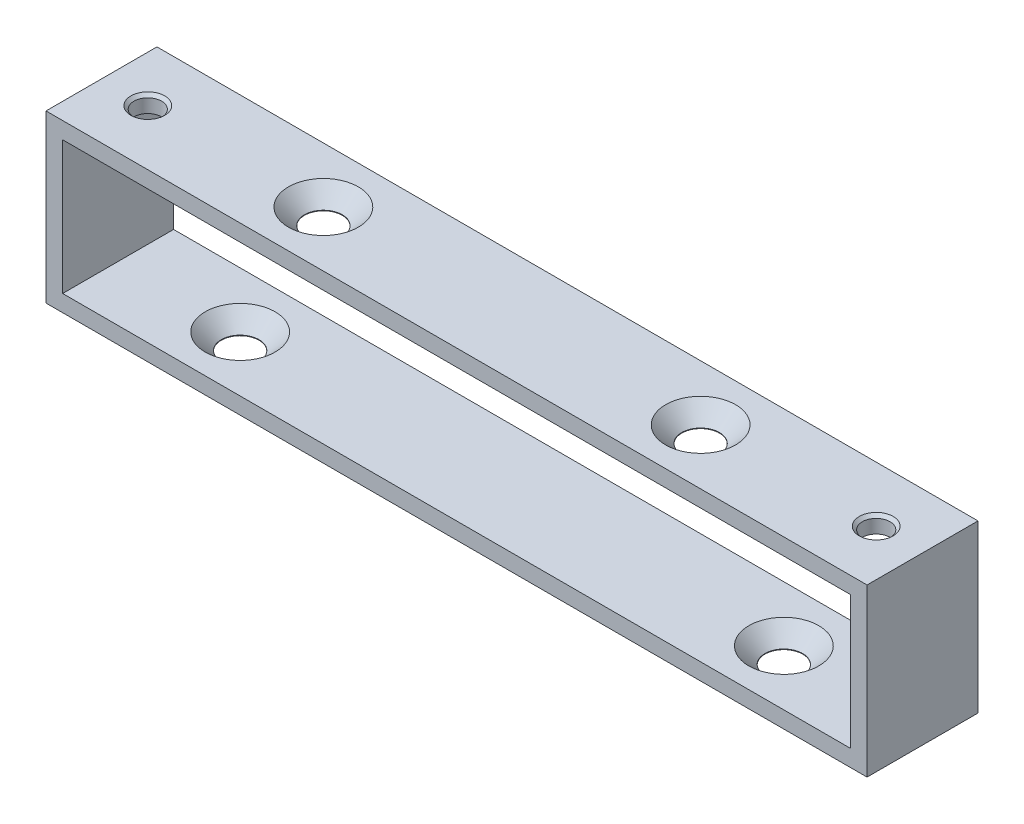
SolidWorks part; units mm, degrees
ref_plane "Ebene vorne" through (0, 0, 0) normal (0, 0, 1) x (1, 0, 0)
ref_plane "Ebene oben" through (0, 0, 0) normal (0, 1, 0) x (1, 0, 0)
ref_plane "Ebene rechts" through (0, 0, 0) normal (1, 0, 0) x (0, 0, -1)
sketch "Skizze1" plane through (0, 0, 0) normal (0, 0, 1) x (1, 0, 0)
  line L1 (-16.6079, 3.6552) -> (57.3921, 3.6552)
  line L2 (-16.6079, 3.6552) -> (-16.6079, -11.3448)
  line L3 (-16.6079, -11.3448) -> (57.3921, -11.3448)
  line L4 (57.3921, 3.6552) -> (57.3921, -11.3448)
  dimension "D1" = 15
  dimension "D2" = 74
extrude "Aufsatz-Linear austragen1" add sketch "Skizze1" along normal blind 10
sketch "Skizze2" plane through (0, 0, 10) normal (0, 0, 1) x (1, 0, 0)
  line L0 (-16.6079, 3.6552) -> (-16.6079, -11.3448) construction
  line L1 (-15.1079, 2.1552) -> (55.8921, 2.1552)
  line L2 (-15.1079, 2.1552) -> (-15.1079, -9.8448)
  line L3 (-15.1079, -9.8448) -> (55.8921, -9.8448)
  line L4 (55.8921, 2.1552) -> (55.8921, -9.8448)
  line L5 (57.3921, 3.6552) -> (-16.6079, 3.6552) construction
  dimension "D1" = 71
  dimension "D2" = 12
  dimension "D3" = 1.5
  dimension "D4" = 1.5
extrude "Schnitt-Linear austragen1" cut sketch "Skizze2" against normal up to next
sketch "Skizze3" plane through (0, 3.6552, 0) normal (0, 1, 0) x (1, 0, 0)
  line L0 (57.3921, -10) -> (-16.6079, -10) construction
  line L1 (57.3921, -10) -> (57.3921, 0) construction
  line L2 (-16.6079, -10) -> (-16.6079, 0) construction
  point P0 (-12.4329, -5)
  point P1 (53.2171, -5)
  dimension "D1" = 5
  dimension "D2" = 65.65
  dimension "D3" = 4.175
  dimension "D4" = 4.175
  dimension "D5" = 5
sketch "Skizze6" plane through (0, -9.8448, 0) normal (0, 1, 0) x (1, 0, 0)
  line L0 (-15.1079, -10) -> (55.8921, -10) construction
  line L1 (-16.6079, -10) -> (-16.6079, 0) construction
  line L2 (57.3921, -10) -> (57.3921, 0) construction
  line L4 (-16.6079, -10) -> (57.3921, -10) construction
  point P0 (-12.4329, -3.63)
  point P1 (53.2171, -3.63)
  dimension "D1" = 6.37
  dimension "D2" = 6.37
  dimension "D3" = 65.65
  dimension "D4" = 4.175
  dimension "D5" = 4.175
sketch "Skizze9" plane through (0, 3.6552, 0) normal (0, 1, 0) x (1, 0, 0)
  line L0 (57.3921, -10) -> (-16.6079, -10) construction
  line L1 (-16.6079, -10) -> (-16.6079, 0) construction
  line L2 (57.3921, -10) -> (57.3921, 0) construction
  point P0 (3.3921, -5)
  point P1 (37.3921, -5)
  dimension "D1" = 5
  dimension "D2" = 5
  dimension "D3" = 20
  dimension "D4" = 20
hole_wizard "Formsenkung für M3 Linsensenkschraube mit Schlitz2" positions "3D-Skizze3" profile "Skizze10" countersink size "M3" standard "ISO" end condition up to next
sketch3d "3D-Skizze3"
  point P0 (3.3921, 3.6552, 5)
  point P3 (37.3921, 3.6552, 5)
sketch "Skizze10" plane through (3.3921, 3.6552, 5) normal (1, 0, 0) x (0, 0, 1)
  line L0 (0, 0) -> (0, 1.5)
  line L1 (0, 1.5) -> (1.7, 1.5)
  line L2 (1.7, 1.5) -> (1.7, 1.45)
  line L3 (1.7, 1.45) -> (3.15, 0)
  line L5 (3.15, 0) -> (0, 0)
  line L6 (-1.7, 1.45) -> (-3.15, 0) construction
  line L11 (0, -6.35) -> (0, 107.95) construction
  dimension "Bohrerdurchmesser" = 3.4
  dimension "Bohrungstiefe" = 1.5
  dimension "Senkdurchmesser (Oben)" = 6.3
  dimension "Senkwinkel (Oben)" = 90
hole_wizard "M3 Gewindebohrung1" positions "3D-Skizze5" profile "Skizze12" tap size "M3" standard "ISO" end condition up to next
sketch3d "3D-Skizze5"
  point P0 (53.2171, 3.6552, 5)
  point P3 (-12.4329, 3.6552, 5)
sketch "Skizze12" plane through (53.2171, 3.6552, 5) normal (1, 0, 0) x (0, 0, 1)
  line L0 (0, 0) -> (0, 1.5)
  line L1 (0, 1.5) -> (1.25, 1.5)
  line L2 (1.25, 1.5) -> (1.25, 0.275)
  line L3 (1.25, 0.275) -> (1.525, 0)
  line L5 (1.525, 0) -> (0, 0)
  line L6 (-1.25, 0.275) -> (-1.525, 0) construction
  line L11 (0, -6.35) -> (0, 107.95) construction
  dimension "Bohrerdurchmesser" = 2.5
  dimension "Bohrungstiefe" = 1.5
  dimension "Senkdurchmesser (Oben)" = 3.05
  dimension "Senkwinkel (Oben)" = 90
cosmetic thread "Bohrungsgewinde1" parameters "D2"=3
cosmetic thread "Bohrungsgewinde2" parameters "D2"=3
sketch "Skizze14" plane through (0, -9.8448, 0) normal (0, -1, 0) x (1, 0, 0)
  line L0 (44.8921, 5) -> (-4.1079, 5)
  line L1 (-16.6079, 0) -> (57.3921, 0) construction
  line L3 (57.3921, 10) -> (57.3921, 0) construction
  line L4 (-16.6079, 10) -> (-16.6079, 0) construction
  dimension "D1" = 49
  dimension "D2" = 5
  dimension "D3" = 12.5
  dimension "D4" = 12.5
hole_wizard "Formsenkung für M3 Linsensenkschraube mit Schlitz3" positions "Skizze15" profile "Skizze16" countersink size "M3" standard "ISO" end condition up to next
sketch "Skizze15" plane through (0, -9.8448, 0) normal (0, 1, 0) x (1, 0, 0)
  point P0 (44.8921, -5)
  point P3 (-4.1079, -5)
sketch "Skizze16" plane through (44.8921, -9.8448, 5) normal (1, 0, 0) x (0, 0, 1)
  line L0 (0, 0) -> (0, 1.5)
  line L1 (0, 1.5) -> (1.7, 1.5)
  line L2 (1.7, 1.5) -> (1.7, 1.45)
  line L3 (1.7, 1.45) -> (3.15, 0)
  line L5 (3.15, 0) -> (0, 0)
  line L6 (-1.7, 1.45) -> (-3.15, 0) construction
  line L11 (0, -6.35) -> (0, 107.95) construction
  dimension "Bohrerdurchmesser" = 3.4
  dimension "Bohrungstiefe" = 1.5
  dimension "Senkdurchmesser (Oben)" = 6.3
  dimension "Senkwinkel (Oben)" = 90
